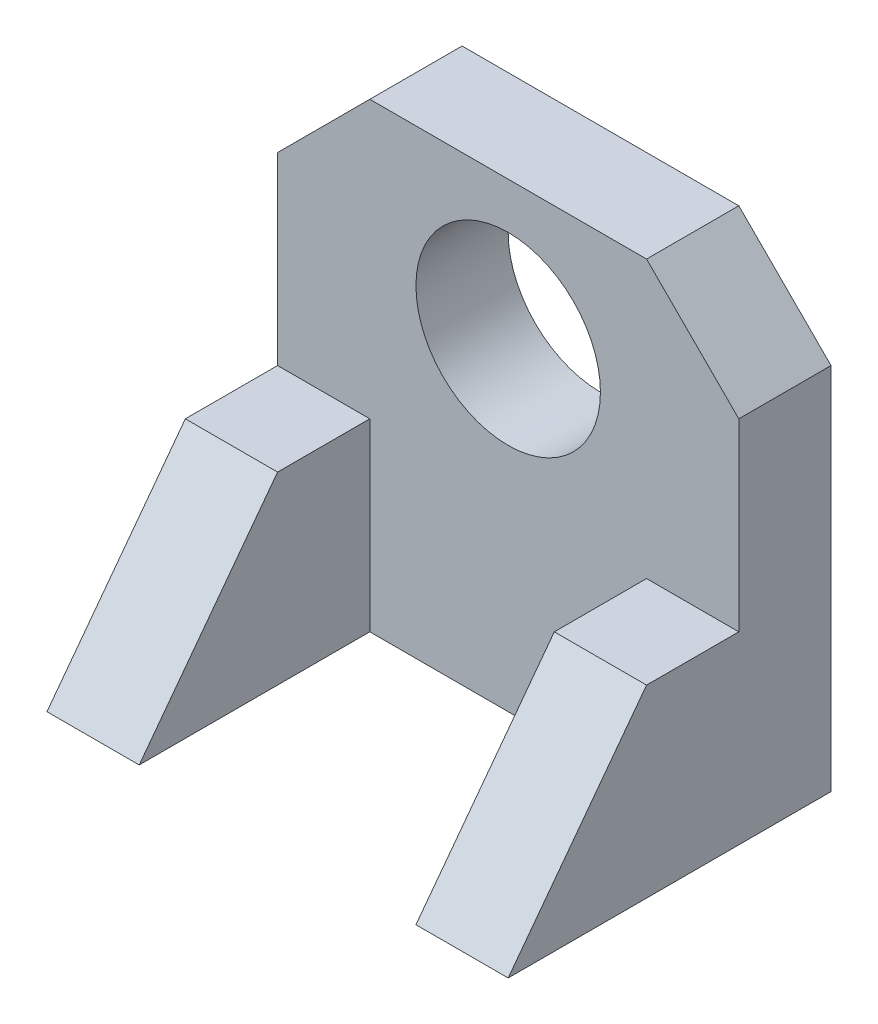
SolidWorks part; units mm, degrees
ref_plane "Front Plane" through (0, 0, 0) normal (0, 0, 1) x (1, 0, 0)
ref_plane "Top Plane" through (0, 0, 0) normal (0, 1, 0) x (1, 0, 0)
ref_plane "Right Plane" through (0, 0, 0) normal (1, 0, 0) x (0, 0, -1)
sketch "Sketch1" plane through (0, 0, 0) normal (0, 0, 1) x (1, 0, 0)
  line L0 (-25, 0) -> (25, 0)
  line L1 (-25, 0) -> (-25, 40)
  line L2 (-25, 40) -> (-15, 50)
  line L3 (-15, 50) -> (15, 50)
  line L4 (15, 50) -> (25, 40)
  line L5 (25, 40) -> (25, 0)
  line L6 (0, 50) -> (0, 35) construction
  circle A0 centre (0, 35) radius 10
  point P0 (0, 50)
  point P4 (0, 0)
  dimension "D9" = 20
  dimension "D1" = 50
  dimension "D2" = 10
  dimension "D3" = 10
  dimension "D4" = 10
  dimension "D5" = 10
  dimension "D6" = 30
  dimension "D7" = 40
  dimension "D8" = 15
extrude "Boss-Extrude1" add sketch "Sketch1" along normal blind 10
sketch "Sketch2" plane through (0, 0, 0) normal (1, 0, 0) x (0, 0, -1)
  line L0 (-10, 20) -> (-20, 20)
  line L1 (-10, 0) -> (-10, 40) construction
  line L2 (-20, 20) -> (-35, 0)
  line L3 (-35, 0) -> (-10, 0)
  line L4 (-10, 20) -> (-10, 0)
  dimension "D1" = 35
  dimension "D2" = 10
  dimension "D3" = 20
extrude "Boss-Extrude2" add sketch "Sketch2" along normal blind 10 from offset 15
mirror "Mirror1" about plane through (0, 0, 0) normal (1, 0, 0) of "Boss-Extrude2"
